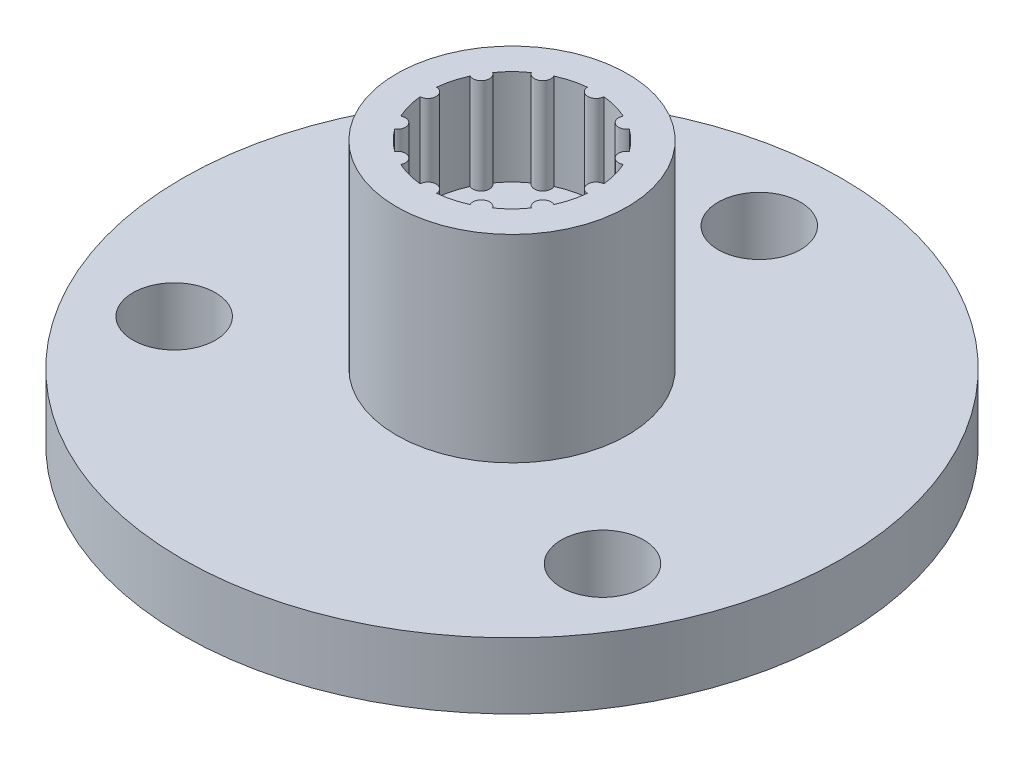
SolidWorks part; units mm, degrees
ref_plane "Front Plane" through (0, 0, 0) normal (0, 0, 1) x (1, 0, 0)
ref_plane "Top Plane" through (0, 0, 0) normal (0, 1, 0) x (1, 0, 0)
ref_plane "Right Plane" through (0, 0, 0) normal (1, 0, 0) x (0, 0, -1)
sketch "Sketch1" plane through (0, 0, 0) normal (0, 1, 0) x (1, 0, 0)
  circle A0 centre (0, 0) radius 10
  circle A1 centre (0, 0) radius 1
  dimension "D1" = 20
  dimension "D2" = 2
extrude "Boss-Extrude1" add sketch "Sketch1" along normal blind 2
sketch "Sketch2" plane through (0, 2, 0) normal (0, 1, 0) x (1, 0, 0)
  circle A0 centre (0, 0) radius 3.5
  circle A1 centre (0, 0) radius 2.55
  dimension "D1" = 7
  dimension "D2" = 5.1
extrude "Boss-Extrude2" add sketch "Sketch2" along normal blind 6
sketch "Sketch3" plane through (0, 2, 0) normal (0, 1, 0) x (1, 0, 0)
  line L0 (0, 0) -> (0, 4.3743) construction
  line L1 (0, 7.5) -> (0, 10) construction
  circle A0 centre (0, 7.5) radius 1.25
  circle A2 centre (0, 0) radius 10 construction
  dimension "D1" = 2.5
  dimension "D2" = 2.5
extrude "Cut-Extrude1" cut sketch "Sketch3" against normal up to next
pattern_circular "CirPattern1" count 3 over 360 about axis through (0, 0, 0) along (0, 1, 0) of "Cut-Extrude1"
sketch "Sketch4" plane through (0, 2, 0) normal (0, 1, 0) x (1, 0, 0)
  circle A0 centre (0, 0) radius 1
  circle A1 centre (0, 0) radius 2.55
  circle A2 centre (0, 0) radius 2.55 construction
  circle A3 centre (0, 0) radius 1 construction
extrude "Boss-Extrude3" add sketch "Sketch4" along normal offset from surface (3.1 mm away) 2.9 up to face at (0, 8, 3.5)
sketch "Sketch5" plane through (0, 0, 0) normal (0, -1, 0) x (1, 0, 0)
  circle A0 centre (0, 0) radius 2
  dimension "D1" = 4
extrude "Cut-Extrude2" cut sketch "Sketch5" against normal offset from surface (4.1 mm away) 1 up to face at (0, 5.1, 1)
sketch "Sketch6" plane through (0, 8, 0) normal (0, 1, 0) x (1, 0, 0)
  line L0 (0, 0) -> (0, 2.55) construction
  arc A0 (-0.2497, 2.5377) -> (0.2497, 2.5377) centre (0, 2.55) ccw
  circle A1 centre (0, 0) radius 2.55 construction
  circle A2 centre (0, 0) radius 2.55 construction
  arc A3 (0.2497, 2.5377) -> (-0.2497, 2.5377) centre (0, 0) ccw
  dimension "D1" = 0.5
extrude "Boss-Extrude4" add sketch "Sketch6" against normal up to surface (2.9 mm away) up to face at (0, 5.1, 1)
pattern_circular "CirPattern2" count 12 over 360 about axis through (0, 0, 0) along (0, 1, 0) of "Boss-Extrude4"
